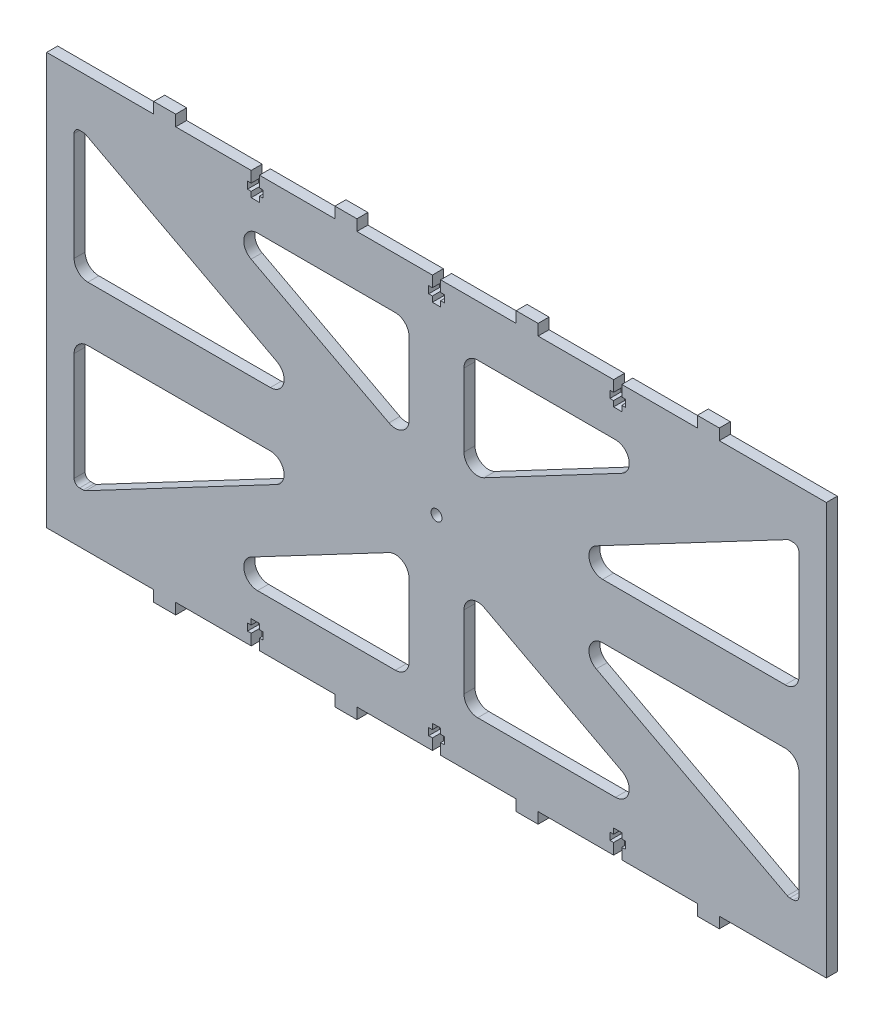
SolidWorks part; units mm, degrees
ref_plane "前视基准面" through (0, 0, 0) normal (0, 0, 1) x (1, 0, 0)
ref_plane "上视基准面" through (0, 0, 0) normal (0, 1, 0) x (1, 0, 0)
ref_plane "右视基准面" through (0, 0, 0) normal (1, 0, 0) x (0, 0, -1)
sketch "草图1" plane through (0, 0, 0) normal (0, 0, 1) x (1, 0, 0)
  line L0 (0, 0) -> (0, -4)
  line L1 (0, -4) -> (-1.35, -4)
  line L2 (-1.35, -4) -> (-1.35, -6.6)
  line L3 (-1.35, -6.6) -> (0, -6.6)
  line L4 (0, -6.6) -> (0, -8.6)
  line L5 (0, -8.6) -> (3, -8.6)
  line L6 (3, -8.6) -> (3, -6.6)
  line L7 (3, -6.6) -> (4.35, -6.6)
  line L8 (4.35, -6.6) -> (4.35, -4)
  line L9 (4.35, -4) -> (3, -4)
  line L10 (3, -4) -> (3, 0)
  line L11 (0, 0) -> (-27.5, 0)
  line L12 (-27.5, 0) -> (-27.5, 4)
  line L13 (-27.5, 4) -> (-35.5, 4)
  line L14 (-35.5, 4) -> (-35.5, 0)
  line L15 (1.5, -8.6) -> (1.5, -6.6) construction
  line L16 (-31.5, 4) -> (-31.5, 0) construction
  line L17 (-67.35, -4) -> (-66, -4)
  line L18 (-66, -6.6) -> (-67.35, -6.6)
  line L19 (-61.65, -6.6) -> (-63, -6.6)
  line L20 (-63, -4) -> (-61.65, -4)
  line L21 (-66, -4) -> (-66, 0)
  line L22 (-66, -8.6) -> (-66, -6.6)
  line L23 (-63, -8.6) -> (-66, -8.6)
  line L24 (-63, -6.6) -> (-63, -8.6)
  line L25 (-67.35, -6.6) -> (-67.35, -4)
  line L26 (-61.65, -4) -> (-61.65, -6.6)
  line L27 (-63, 0) -> (-63, -4)
  line L28 (-63, 0) -> (-35.5, 0)
  line L29 (30.5, 4) -> (38.5, 4)
  line L30 (30.5, 0) -> (30.5, 4)
  line L31 (38.5, 4) -> (38.5, 0)
  line L32 (3, 0) -> (30.5, 0)
  line L33 (66, 0) -> (38.5, 0)
  line L34 (66, 0) -> (66, -4)
  line L35 (64.65, -4) -> (64.65, -6.6)
  line L36 (70.35, -6.6) -> (70.35, -4)
  line L37 (66, -6.6) -> (66, -8.6)
  line L38 (66, -8.6) -> (69, -8.6)
  line L39 (69, -8.6) -> (69, -6.6)
  line L40 (69, -4) -> (69, 0)
  line L41 (66, -4) -> (64.65, -4)
  line L42 (64.65, -6.6) -> (66, -6.6)
  line L43 (69, -6.6) -> (70.35, -6.6)
  line L44 (70.35, -4) -> (69, -4)
  line L45 (67.5, -8.6) -> (67.5, -6.6) construction
  line L46 (69, 0) -> (96.5, 0)
  line L47 (132, 0) -> (104.5, 0)
  line L48 (96.5, 4) -> (96.5, 0)
  line L49 (104.5, 0) -> (104.5, 4)
  line L50 (104.5, 4) -> (96.5, 4)
  line L51 (-64.5, -8.6) -> (-64.5, -6.6) construction
  line L52 (-97.5, 4) -> (-97.5, 0) construction
  line L53 (-66, 0) -> (-93.5, 0)
  line L54 (-93.5, 4) -> (-93.5, 0)
  line L55 (-101.5, 4) -> (-93.5, 4)
  line L56 (-101.5, 0) -> (-101.5, 4)
  line L57 (-129, 0) -> (-101.5, 0)
  line L58 (1.5, -8.6) -> (-140.5, -8.6) construction
  line L59 (-129, 0) -> (-140.5, 0)
  line L60 (132, 0) -> (143.5, 0)
  line L61 (-140.5, 0) -> (-140.5, -150)
  line L63 (143.5, -150) -> (143.5, 0)
  line L64 (143.5, -75) -> (115.133, -75) construction
  line L65 (-129, -150) -> (-140.5, -150)
  line L66 (1.5, -141.4) -> (1.5, -143.4) construction
  line L67 (3, -146) -> (3, -150)
  line L68 (4.35, -146) -> (3, -146)
  line L69 (4.35, -143.4) -> (4.35, -146)
  line L70 (3, -143.4) -> (4.35, -143.4)
  line L71 (3, -141.4) -> (3, -143.4)
  line L72 (0, -141.4) -> (3, -141.4)
  line L73 (0, -143.4) -> (0, -141.4)
  line L74 (-1.35, -143.4) -> (0, -143.4)
  line L75 (-1.35, -146) -> (-1.35, -143.4)
  line L76 (0, -146) -> (-1.35, -146)
  line L77 (0, -150) -> (0, -146)
  line L78 (132, -150) -> (143.5, -150)
  line L79 (67.5, -141.4) -> (67.5, -143.4) construction
  line L80 (104.5, -154) -> (96.5, -154)
  line L81 (104.5, -150) -> (104.5, -154)
  line L82 (96.5, -154) -> (96.5, -150)
  line L83 (132, -150) -> (104.5, -150)
  line L84 (69, -150) -> (96.5, -150)
  line L85 (70.35, -146) -> (69, -146)
  line L86 (69, -143.4) -> (70.35, -143.4)
  line L87 (64.65, -143.4) -> (66, -143.4)
  line L88 (66, -146) -> (64.65, -146)
  line L89 (69, -146) -> (69, -150)
  line L90 (69, -141.4) -> (69, -143.4)
  line L91 (66, -141.4) -> (69, -141.4)
  line L92 (66, -143.4) -> (66, -141.4)
  line L93 (70.35, -143.4) -> (70.35, -146)
  line L94 (64.65, -146) -> (64.65, -143.4)
  line L95 (66, -150) -> (66, -146)
  line L96 (66, -150) -> (38.5, -150)
  line L97 (3, -150) -> (30.5, -150)
  line L98 (38.5, -154) -> (38.5, -150)
  line L99 (30.5, -150) -> (30.5, -154)
  line L100 (30.5, -154) -> (38.5, -154)
  line L101 (1.5, -141.4) -> (-140.5, -141.4) construction
  line L102 (-97.5, -154) -> (-97.5, -150) construction
  line L103 (-64.5, -141.4) -> (-64.5, -143.4) construction
  line L104 (-31.5, -154) -> (-31.5, -150) construction
  line L105 (-129, -150) -> (-101.5, -150)
  line L106 (-101.5, -150) -> (-101.5, -154)
  line L107 (-101.5, -154) -> (-93.5, -154)
  line L108 (-93.5, -154) -> (-93.5, -150)
  line L109 (-66, -150) -> (-93.5, -150)
  line L110 (-63, -150) -> (-35.5, -150)
  line L111 (-63, -150) -> (-63, -146)
  line L112 (-61.65, -146) -> (-61.65, -143.4)
  line L113 (-67.35, -143.4) -> (-67.35, -146)
  line L114 (-63, -143.4) -> (-63, -141.4)
  line L115 (-63, -141.4) -> (-66, -141.4)
  line L116 (-66, -141.4) -> (-66, -143.4)
  line L117 (-66, -146) -> (-66, -150)
  line L118 (-63, -146) -> (-61.65, -146)
  line L119 (-61.65, -143.4) -> (-63, -143.4)
  line L120 (-66, -143.4) -> (-67.35, -143.4)
  line L121 (-67.35, -146) -> (-66, -146)
  line L122 (-35.5, -154) -> (-35.5, -150)
  line L123 (-27.5, -154) -> (-35.5, -154)
  line L124 (-27.5, -150) -> (-27.5, -154)
  line L125 (0, -150) -> (-27.5, -150)
  dimension "D1" = 3
  dimension "D2" = 2
  dimension "D3" = 4
  dimension "D4" = 2.6
  dimension "D5" = 1.35
extrude "凸台-拉伸1" add sketch "草图1" along normal blind 4 contours L61 L63 L60 L47 L49 L50 L48 L46 L40 L44 L36 L43 L39 L38 L37 L42 L35 L41 L34 L33 L31 L29 L30 L32 L10 L9 L8 L7 L6 L5 L4 L3 L2 L1 L0 L11 L12 L13 L14 L28 L27 L20 L26 L19 L24 L23 L22 L18 L25 L17 L21 L53 L54 L55 L56 L57 L59
sketch "草图2" plane through (0, 0, 0) normal (0, 1, 0) x (1, 0, 0)
  line L0 (3, -2) -> (0, -2)
  line L1 (3, -4) -> (3, 0) construction
  line L2 (0, -4) -> (0, 0) construction
  circle A0 centre (1.5, -2) radius 1.5
sketch "草图3" plane through (0, -150, 0) normal (0, -1, 0) x (1, 0, 0)
  line L0 (3, 2) -> (0, 2)
  line L1 (3, 4) -> (3, 0) construction
  line L2 (0, 4) -> (0, 0) construction
  circle A0 centre (1.5, 2) radius 1.5
sketch "草图4" plane through (0, 0, 4) normal (0, 0, 1) x (1, 0, 0)
  line L4 (18.8351, -95.465) -> (69.0346, -121.9788)
  line L5 (16.5, -131.4) -> (66.6994, -131.4)
  line L6 (11.5, -99.8862) -> (11.5, -126.4)
  line L10 (-8.5, -99.8862) -> (-8.5, -126.4)
  line L11 (-13.5, -131.4) -> (-63.6994, -131.4)
  line L12 (-15.8351, -95.465) -> (-66.0346, -121.9788)
  line L14 (143.5, -150) -> (143.5, 0) construction
  line L15 (143.5, -141.4) -> (143.5, -75)
  line L16 (143.5, -141.4) -> (127.2173, -141.4)
  line L17 (133.5, -129.4) -> (133.5, -90)
  line L20 (62.0179, -85) -> (128.5, -85)
  line L21 (59.6828, -94.4212) -> (129.2576, -131.1685)
  line L22 (131.5, -131.4) -> (130.1917, -131.4)
  line L23 (133.5, -131.4) -> (133.5, -85) construction
  line L24 (41.8453, -85) -> (133.5, -85) construction
  line L25 (41.8453, -85) -> (129.6959, -131.4) construction
  line L26 (133.5, -131.4) -> (129.6959, -131.4) construction
  line L27 (131.5, -18.6) -> (130.1917, -18.6)
  line L28 (59.6828, -55.5788) -> (129.2576, -18.8315)
  line L29 (62.0179, -65) -> (128.5, -65)
  line L30 (133.5, -20.6) -> (133.5, -60)
  line L31 (11.5, -50.1138) -> (11.5, -23.6)
  line L32 (16.5, -18.6) -> (66.6994, -18.6)
  line L33 (18.8351, -54.535) -> (69.0346, -28.0212)
  line L34 (-15.8351, -54.535) -> (-66.0346, -28.0212)
  line L35 (-13.5, -18.6) -> (-63.6994, -18.6)
  line L36 (-8.5, -50.1138) -> (-8.5, -23.6)
  line L37 (1.5, -75) -> (1.5, -60) construction
  line L38 (-128.5, -131.4) -> (-127.1917, -131.4)
  line L39 (-56.6828, -94.4212) -> (-126.2576, -131.1685)
  line L40 (-59.0179, -85) -> (-125.5, -85)
  line L41 (-130.5, -129.4) -> (-130.5, -90)
  line L42 (-130.5, -20.6) -> (-130.5, -60)
  line L43 (-59.0179, -65) -> (-125.5, -65)
  line L44 (-56.6828, -55.5788) -> (-126.2576, -18.8315)
  line L45 (-128.5, -18.6) -> (-127.1917, -18.6)
  line L46 (1.5, -75) -> (143.5, -75) construction
  line L47 (1.5, -75) -> (127.2173, -141.4) construction
  arc A0 (69.0346, -121.9788) -> (66.6994, -131.4) centre (66.6994, -126.4) cw
  arc A1 (16.5, -131.4) -> (11.5, -126.4) centre (16.5, -126.4) cw
  arc A2 (18.8351, -95.465) -> (11.5, -99.8862) centre (16.5, -99.8862) ccw
  arc A3 (-15.8351, -95.465) -> (-8.5, -99.8862) centre (-13.5, -99.8862) cw
  arc A4 (-13.5, -131.4) -> (-8.5, -126.4) centre (-13.5, -126.4) ccw
  arc A5 (-66.0346, -121.9788) -> (-63.6994, -131.4) centre (-63.6994, -126.4) ccw
  arc A6 (133.5, -90) -> (128.5, -85) centre (128.5, -90) ccw
  arc A7 (62.0179, -85) -> (59.6828, -94.4212) centre (62.0179, -90) ccw
  arc A8 (131.5, -131.4) -> (133.5, -129.4) centre (131.5, -129.4) ccw
  arc A9 (130.1917, -131.4) -> (129.2576, -131.1685) centre (130.1917, -129.4) cw
  arc A10 (130.1917, -18.6) -> (129.2576, -18.8315) centre (130.1917, -20.6) ccw
  arc A11 (131.5, -18.6) -> (133.5, -20.6) centre (131.5, -20.6) cw
  arc A12 (62.0179, -65) -> (59.6828, -55.5788) centre (62.0179, -60) cw
  arc A13 (133.5, -60) -> (128.5, -65) centre (128.5, -60) cw
  arc A14 (18.8351, -54.535) -> (11.5, -50.1138) centre (16.5, -50.1138) cw
  arc A15 (16.5, -18.6) -> (11.5, -23.6) centre (16.5, -23.6) ccw
  arc A16 (69.0346, -28.0212) -> (66.6994, -18.6) centre (66.6994, -23.6) ccw
  arc A17 (-66.0346, -28.0212) -> (-63.6994, -18.6) centre (-63.6994, -23.6) cw
  arc A18 (-13.5, -18.6) -> (-8.5, -23.6) centre (-13.5, -23.6) cw
  arc A19 (-15.8351, -54.535) -> (-8.5, -50.1138) centre (-13.5, -50.1138) ccw
  arc A20 (-127.1917, -131.4) -> (-126.2576, -131.1685) centre (-127.1917, -129.4) ccw
  arc A21 (-128.5, -131.4) -> (-130.5, -129.4) centre (-128.5, -129.4) cw
  arc A22 (-59.0179, -85) -> (-56.6828, -94.4212) centre (-59.0179, -90) cw
  arc A23 (-130.5, -90) -> (-125.5, -85) centre (-125.5, -90) cw
  arc A24 (-130.5, -60) -> (-125.5, -65) centre (-125.5, -60) ccw
  arc A25 (-59.0179, -65) -> (-56.6828, -55.5788) centre (-59.0179, -60) ccw
  arc A26 (-128.5, -18.6) -> (-130.5, -20.6) centre (-128.5, -20.6) ccw
  arc A27 (-127.1917, -18.6) -> (-126.2576, -18.8315) centre (-127.1917, -20.6) cw
  circle A28 centre (1.5, -75) radius 2
  dimension "D2" = 5
  dimension "D4" = 5
  dimension "D5" = 2
  dimension "D3" = 10
extrude "切除-拉伸1" cut sketch "草图4" against normal blind 10 contours A27 L45 A26 L42 A24 L43 A25 L44 | A23 L41 A21 L38 A20 L39 A22 L40 | L12 A5 L11 A4 L10 A3 | L4 A2 L6 A1 L5 A0 | A9 L22 A8 L17 A6 L20 A7 L21 | A13 L30 A11 L27 A10 L28 A12 L29 | L33 A16 L32 A15 L31 A14 | L34 A19 L36 A18 L35 A17 | A28
